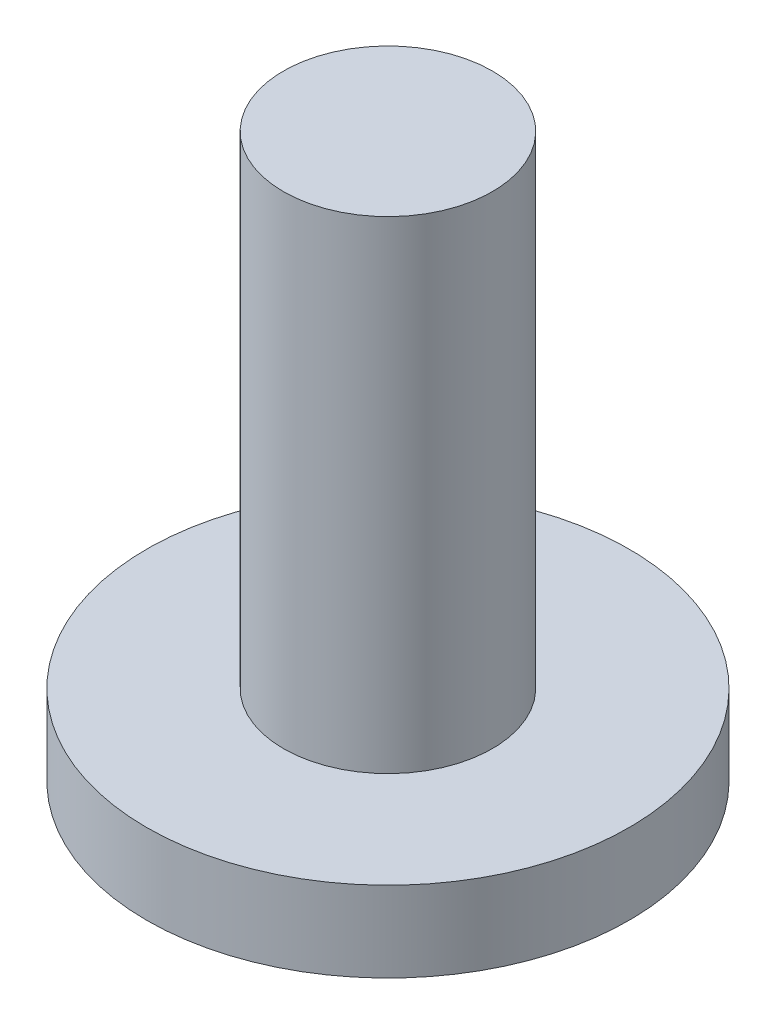
SolidWorks part; units mm, degrees
ref_plane "Front Plane" through (0, 0, 0) normal (0, 0, 1) x (1, 0, 0)
ref_plane "Top Plane" through (0, 0, 0) normal (0, 1, 0) x (1, 0, 0)
ref_plane "Right Plane" through (0, 0, 0) normal (1, 0, 0) x (0, 0, -1)
sketch "Sketch1" plane through (0, 0, 0) normal (0, 1, 0) x (1, 0, 0)
  circle A0 centre (0, 0) radius 3
  dimension "D1" = 6
extrude "Boss-Extrude1" add sketch "Sketch1" along normal blind 1
sketch "Sketch2" plane through (0, 1, 0) normal (0, 1, 0) x (1, 0, 0)
  circle A0 centre (0, 0) radius 1.3
  dimension "D1" = 2.6
extrude "Boss-Extrude2" add sketch "Sketch2" along normal blind 6
